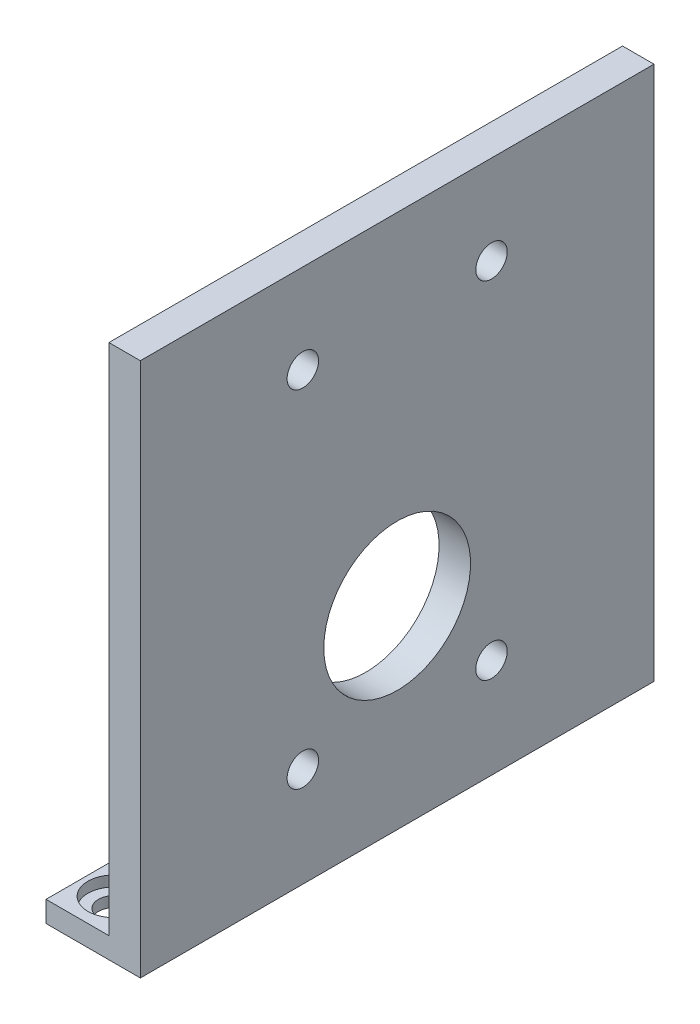
SolidWorks part; units mm, degrees
ref_plane "Front Plane" through (0, 0, 0) normal (0, 0, 1) x (1, 0, 0)
ref_plane "Top Plane" through (0, 0, 0) normal (0, 1, 0) x (1, 0, 0)
ref_plane "Right Plane" through (0, 0, 0) normal (1, 0, 0) x (0, 0, -1)
sketch "Sketch1" plane through (0, 0, 0) normal (0, 1, 0) x (1, 0, 0)
  line L1 (-4.5, 24.5) -> (4.5, 24.5)
  line L2 (-4.5, 24.5) -> (-4.5, -24.5)
  line L3 (-4.5, -24.5) -> (4.5, -24.5)
  line L4 (4.5, 24.5) -> (4.5, -24.5)
  line L5 (-4.5, 24.5) -> (4.5, -24.5) construction
  line L6 (-4.5, -24.5) -> (4.5, 24.5) construction
  point P0 (0, 0)
  dimension "D1" = 9
  dimension "D2" = 49
extrude "Boss-Extrude1" add sketch "Sketch1" along normal blind 2
sketch "Sketch2" plane through (0, 2, 0) normal (0, 1, 0) x (1, 0, 0)
  line L0 (1.5, 24.5) -> (1.5, -24.5) construction
  line L1 (4.5, 24.5) -> (-4.5, 24.5) construction
  line L2 (-4.5, -24.5) -> (4.5, -24.5) construction
  line L3 (4.5, -24.5) -> (4.5, 24.5) construction
  line L5 (4.5, 24.5) -> (1.5, 24.5)
  line L6 (4.5, 24.5) -> (4.5, -24.5)
  line L7 (4.5, -24.5) -> (1.5, -24.5)
  line L8 (1.5, 24.5) -> (1.5, -24.5)
  dimension "D1" = 3
extrude "Boss-Extrude2" add sketch "Sketch2" along normal blind 49
sketch "Sketch3" plane through (1.5, 0, 0) normal (-1, 0, 0) x (0, 0, 1)
  line L0 (-24.5, 49.5) -> (24.5, 49.5) construction
  line L1 (-24.5, 51) -> (-24.5, 2) construction
  line L2 (24.5, 51) -> (24.5, 2) construction
  line L3 (-24.5, 51) -> (24.5, 51) construction
  line L4 (-24.5, 3.5) -> (24.5, 3.5) construction
  line L5 (-24.5, 2) -> (24.5, 2) construction
  line L6 (-23, 51) -> (-23, 2) construction
  line L7 (23, 51) -> (23, 2) construction
  line L8 (-24.5, 2) -> (24.5, 2) construction
  line L9 (0, 51) -> (0, 3.5) construction
  circle A0 centre (0, 18.5) radius 7
  circle A1 centre (-9, 9.5) radius 1.5
  circle A2 centre (9, 9.5) radius 1.5
  circle A3 centre (-9, 42.5) radius 1.5
  circle A4 centre (9, 42.5) radius 1.5
  dimension "D5" = 14
  dimension "D7" = 6
  dimension "D11" = 7
  dimension "D1" = 1.5
  dimension "D2" = 1.5
  dimension "D3" = 1.5
  dimension "D4" = 1.5
  dimension "D6" = 15
  dimension "D8" = 6
  dimension "D9" = 9
  dimension "D10" = 9
  dimension "D12" = 7
extrude "Cut-Extrude1" cut sketch "Sketch3" against normal blind 3
sketch "Sketch4" plane through (0, 2, 0) normal (0, 1, 0) x (1, 0, 0)
  line L0 (-1.5, 24.5) -> (-1.5, -24.5) construction
  line L1 (1.5, 24.5) -> (-4.5, 24.5) construction
  line L2 (-4.5, -24.5) -> (1.5, -24.5) construction
  circle A0 centre (-1.5, 21) radius 2.5
  circle A1 centre (-1.5, -21) radius 2.5
  dimension "D1" = 3.5
  dimension "D2" = 3.5
extrude "Cut-Extrude2" cut sketch "Sketch4" against normal blind 1
sketch "Sketch5" plane through (0, 1, 0) normal (0, 1, 0) x (1, 0, 0)
  circle A0 centre (-1.5, 21) radius 1.5
extrude "Cut-Extrude3" cut sketch "Sketch5" against normal blind 2
sketch "Sketch6" plane through (0, 1, 0) normal (0, 1, 0) x (1, 0, 0)
  circle A0 centre (-1.5, -21) radius 1.5
extrude "Cut-Extrude4" cut sketch "Sketch6" against normal blind 2
